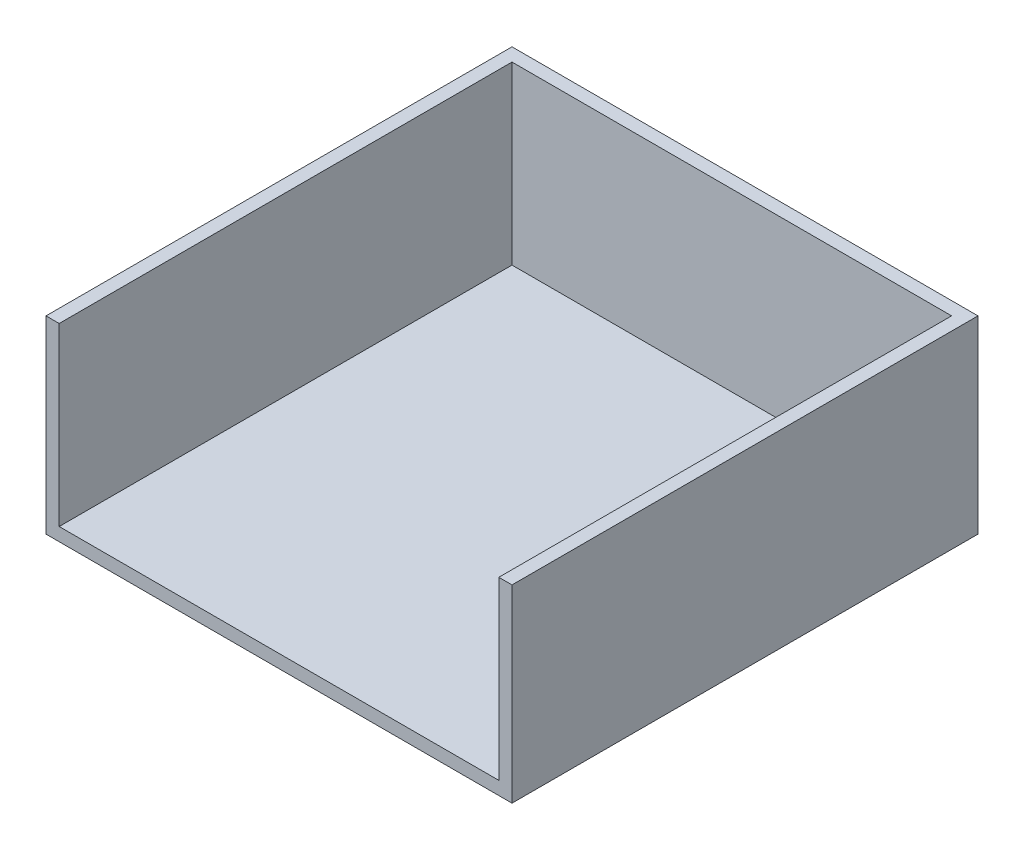
SolidWorks part; units mm, degrees
ref_plane "Front Plane" through (0, 0, 0) normal (0, 0, 1) x (1, 0, 0)
ref_plane "Top Plane" through (0, 0, 0) normal (0, 1, 0) x (1, 0, 0)
ref_plane "Right Plane" through (0, 0, 0) normal (1, 0, 0) x (0, 0, -1)
sketch "Sketch1" plane through (0, 0, 0) normal (0, 1, 0) x (1, 0, 0)
  line L1 (0, 0) -> (53, 0)
  line L2 (0, 0) -> (0, 53)
  line L3 (0, 53) -> (53, 53)
  line L4 (53, 0) -> (53, 53)
  dimension "D1" = 53
  dimension "D2" = 53
extrude "Boss-Extrude1" add sketch "Sketch1" along normal blind 1.5
sketch "Sketch3" plane through (0, 1.5, 0) normal (0, 1, 0) x (1, 0, 0)
  line L0 (0, 0) -> (0, 53)
  line L1 (0, 53) -> (53, 53)
  line L2 (53, 53) -> (53, 0)
  line L3 (53, 0) -> (51.5, 0)
  line L4 (0, 0) -> (53, 0) construction
  line L5 (51.5, 0) -> (51.5, 51.5)
  line L6 (51.5, 51.5) -> (1.5, 51.5)
  line L7 (1.5, 51.5) -> (1.5, 0)
  line L8 (1.5, 0) -> (0, 0)
  point P4 (1.5, 51.5)
  point P15 (0, 0)
  dimension "D1" = 1.5
  dimension "D2" = 1.5
  dimension "D3" = 1.5
extrude "Boss-Extrude2" add sketch "Sketch3" along normal blind 20
